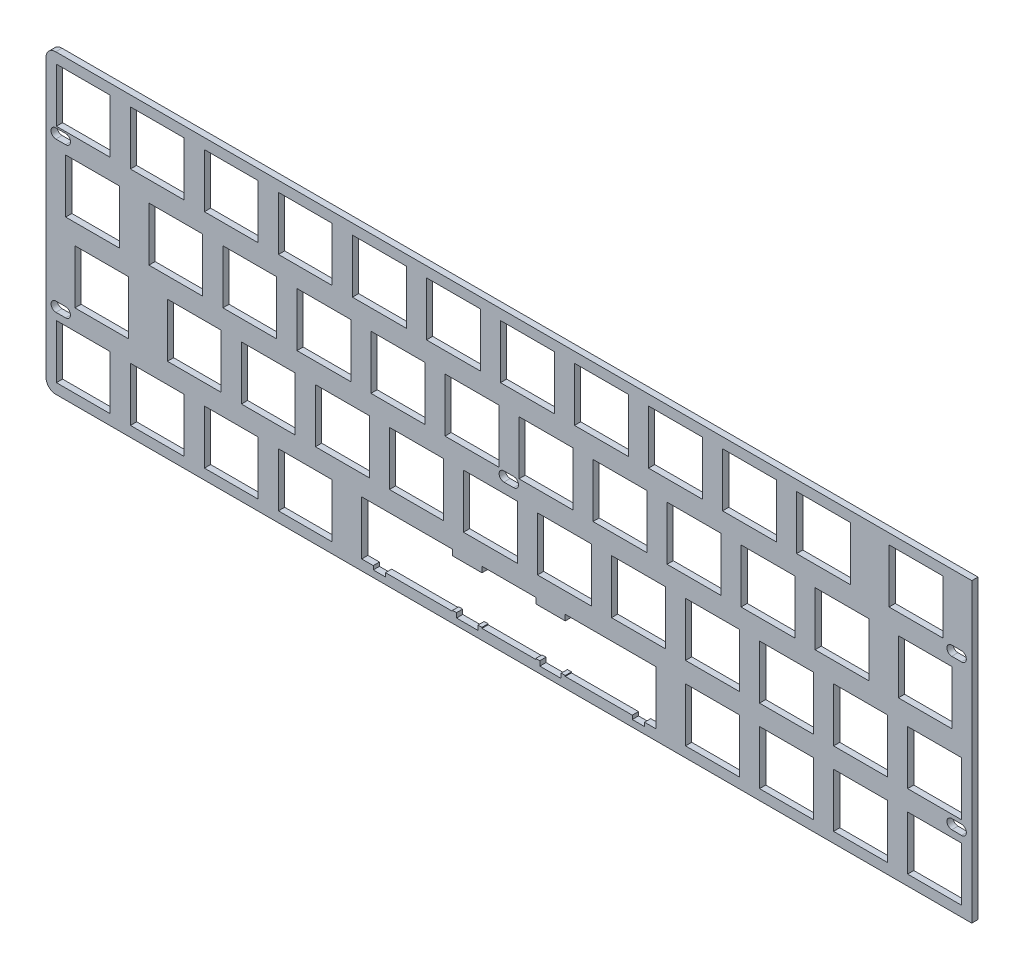
SolidWorks part; units mm, degrees
ref_plane "Front Plane" through (0, 0, 0) normal (0, 0, 1) x (1, 0, 0)
ref_plane "Top Plane" through (0, 0, 0) normal (0, 1, 0) x (1, 0, 0)
ref_plane "Right Plane" through (0, 0, 0) normal (1, 0, 0) x (0, 0, -1)
sketch "Model" plane through (0, 0, 0) normal (0, 0, 1) x (1, 0, 0)
  line L0 (0.0951, 76.4575) -> (238.37, 76.4575)
  line L1 (238.37, 76.4575) -> (238.37, 0.1075)
  line L2 (238.37, 0.1075) -> (0.0951, 0.1075)
  line L3 (0.0951, 0.1075) -> (0.0951, 76.4575)
  line L4 (81.3513, 16.6329) -> (81.3513, 2.7836)
  line L5 (81.3513, 2.7836) -> (84.3248, 2.7836)
  line L6 (84.3248, 2.7836) -> (84.3248, 1.8135)
  line L7 (84.3248, 1.8135) -> (87.4751, 1.8135)
  line L8 (87.4751, 1.8135) -> (87.4751, 2.7836)
  line L9 (87.4751, 2.7836) -> (104.725, 2.7836)
  line L10 (104.725, 2.7836) -> (104.725, 3.0138)
  line L11 (104.725, 3.0138) -> (105.756, 3.0138)
  line L12 (105.756, 3.0138) -> (105.756, 1.8135)
  line L13 (105.756, 1.8135) -> (111.275, 1.8135)
  line L14 (111.275, 1.8135) -> (111.275, 3.0138)
  line L15 (111.275, 3.0138) -> (112.306, 3.0138)
  line L16 (112.306, 3.0138) -> (112.306, 2.7836)
  line L17 (112.306, 2.7836) -> (126.157, 2.7836)
  line L18 (126.157, 2.7836) -> (126.157, 3.0138)
  line L19 (126.157, 3.0138) -> (127.187, 3.0138)
  line L20 (127.187, 3.0138) -> (127.187, 1.8135)
  line L21 (127.187, 1.8135) -> (132.707, 1.8135)
  line L22 (132.707, 1.8135) -> (132.707, 3.0138)
  line L23 (132.707, 3.0138) -> (133.737, 3.0138)
  line L24 (133.737, 3.0138) -> (133.737, 2.7836)
  line L25 (133.737, 2.7836) -> (150.987, 2.7836)
  line L26 (150.987, 2.7836) -> (150.987, 1.8135)
  line L27 (150.987, 1.8135) -> (154.138, 1.8135)
  line L28 (154.138, 1.8135) -> (154.138, 2.7836)
  line L29 (154.138, 2.7836) -> (157.113, 2.7836)
  line L30 (157.113, 2.7836) -> (157.113, 16.6329)
  line L31 (157.113, 16.6329) -> (133.737, 16.6329)
  line L32 (133.737, 16.6329) -> (133.737, 15.1639)
  line L33 (133.737, 15.1639) -> (126.157, 15.1639)
  line L34 (126.157, 15.1639) -> (126.157, 16.6329)
  line L35 (126.157, 16.6329) -> (112.306, 16.6329)
  line L36 (112.306, 16.6329) -> (112.306, 15.1639)
  line L37 (112.306, 15.1639) -> (104.725, 15.1639)
  line L38 (104.725, 15.1639) -> (104.725, 16.6329)
  line L39 (104.725, 16.6329) -> (81.3513, 16.6329)
  line L40 (221.845, 16.6329) -> (235.694, 16.6329)
  line L41 (235.694, 16.6329) -> (235.694, 2.7836)
  line L42 (235.694, 2.7836) -> (221.845, 2.7836)
  line L43 (221.845, 2.7836) -> (221.845, 16.6329)
  line L44 (202.795, 16.6329) -> (216.644, 16.6329)
  line L45 (216.644, 16.6329) -> (216.644, 2.7836)
  line L46 (216.644, 2.7836) -> (202.795, 2.7836)
  line L47 (202.795, 2.7836) -> (202.795, 16.6329)
  line L48 (183.745, 16.6329) -> (197.594, 16.6329)
  line L49 (197.594, 16.6329) -> (197.594, 2.7836)
  line L50 (197.594, 2.7836) -> (183.745, 2.7836)
  line L51 (183.745, 2.7836) -> (183.745, 16.6329)
  line L52 (164.695, 16.6329) -> (178.544, 16.6329)
  line L53 (178.544, 16.6329) -> (178.544, 2.7836)
  line L54 (178.544, 2.7836) -> (164.695, 2.7836)
  line L55 (164.695, 2.7836) -> (164.695, 16.6329)
  line L56 (59.92, 16.6329) -> (73.769, 16.6329)
  line L57 (73.769, 16.6329) -> (73.769, 2.7836)
  line L58 (73.769, 2.7836) -> (59.92, 2.7836)
  line L59 (59.92, 2.7836) -> (59.92, 16.6329)
  line L60 (40.87, 16.6329) -> (54.719, 16.6329)
  line L61 (54.719, 16.6329) -> (54.719, 2.7836)
  line L62 (54.719, 2.7836) -> (40.87, 2.7836)
  line L63 (40.87, 2.7836) -> (40.87, 16.6329)
  line L64 (21.8199, 16.6329) -> (35.669, 16.6329)
  line L65 (35.669, 16.6329) -> (35.669, 2.7836)
  line L66 (35.669, 2.7836) -> (21.8199, 2.7836)
  line L67 (21.8199, 2.7836) -> (21.8199, 16.6329)
  line L68 (2.7699, 16.6329) -> (16.6192, 16.6329)
  line L69 (16.6192, 16.6329) -> (16.6192, 2.7836)
  line L70 (16.6192, 2.7836) -> (2.7699, 2.7836)
  line L71 (2.7699, 2.7836) -> (2.7699, 16.6329)
  line L72 (221.845, 35.6828) -> (235.694, 35.6828)
  line L73 (235.694, 35.6828) -> (235.694, 21.8336)
  line L74 (235.694, 21.8336) -> (221.845, 21.8336)
  line L75 (221.845, 21.8336) -> (221.845, 35.6828)
  line L76 (202.795, 35.6828) -> (216.644, 35.6828)
  line L77 (216.644, 35.6828) -> (216.644, 21.8336)
  line L78 (216.644, 21.8336) -> (202.795, 21.8336)
  line L79 (202.795, 21.8336) -> (202.795, 35.6828)
  line L80 (183.745, 35.6828) -> (197.594, 35.6828)
  line L81 (197.594, 35.6828) -> (197.594, 21.8336)
  line L82 (197.594, 21.8336) -> (183.745, 21.8336)
  line L83 (183.745, 21.8336) -> (183.745, 35.6828)
  line L84 (164.695, 35.6828) -> (178.544, 35.6828)
  line L85 (178.544, 35.6828) -> (178.544, 21.8336)
  line L86 (178.544, 21.8336) -> (164.695, 21.8336)
  line L87 (164.695, 21.8336) -> (164.695, 35.6828)
  line L88 (145.644, 35.6828) -> (159.494, 35.6828)
  line L89 (159.494, 35.6828) -> (159.494, 21.8336)
  line L90 (159.494, 21.8336) -> (145.644, 21.8336)
  line L91 (145.644, 21.8336) -> (145.644, 35.6828)
  line L92 (126.594, 35.6828) -> (140.444, 35.6828)
  line L93 (140.444, 35.6828) -> (140.444, 21.8336)
  line L94 (140.444, 21.8336) -> (126.594, 21.8336)
  line L95 (126.594, 21.8336) -> (126.594, 35.6828)
  line L96 (107.544, 35.6828) -> (121.394, 35.6828)
  line L97 (121.394, 35.6828) -> (121.394, 21.8336)
  line L98 (121.394, 21.8336) -> (107.544, 21.8336)
  line L99 (107.544, 21.8336) -> (107.544, 35.6828)
  line L100 (88.4936, 35.6828) -> (102.344, 35.6828)
  line L101 (102.344, 35.6828) -> (102.344, 21.8336)
  line L102 (102.344, 21.8336) -> (88.4936, 21.8336)
  line L103 (88.4936, 21.8336) -> (88.4936, 35.6828)
  line L104 (69.445, 35.6828) -> (83.294, 35.6828)
  line L105 (83.294, 35.6828) -> (83.294, 21.8336)
  line L106 (83.294, 21.8336) -> (69.445, 21.8336)
  line L107 (69.445, 21.8336) -> (69.445, 35.6828)
  line L108 (50.395, 35.6828) -> (64.244, 35.6828)
  line L109 (64.244, 35.6828) -> (64.244, 21.8336)
  line L110 (64.244, 21.8336) -> (50.395, 21.8336)
  line L111 (50.395, 21.8336) -> (50.395, 35.6828)
  line L112 (31.3449, 35.6828) -> (45.194, 35.6828)
  line L113 (45.194, 35.6828) -> (45.194, 21.8336)
  line L114 (45.194, 21.8336) -> (31.3449, 21.8336)
  line L115 (31.3449, 21.8336) -> (31.3449, 35.6828)
  line L116 (7.531, 35.6828) -> (21.3817, 35.6828)
  line L117 (21.3817, 35.6828) -> (21.3817, 21.8336)
  line L118 (21.3817, 21.8336) -> (7.531, 21.8336)
  line L119 (7.531, 21.8336) -> (7.531, 35.6828)
  line L120 (219.462, 54.7328) -> (233.313, 54.7328)
  line L121 (233.313, 54.7328) -> (233.313, 40.8838)
  line L122 (233.313, 40.8838) -> (219.462, 40.8838)
  line L123 (219.462, 40.8838) -> (219.462, 54.7328)
  line L124 (198.031, 54.7328) -> (211.882, 54.7328)
  line L125 (211.882, 54.7328) -> (211.882, 40.8838)
  line L126 (211.882, 40.8838) -> (198.031, 40.8838)
  line L127 (198.031, 40.8838) -> (198.031, 54.7328)
  line L128 (178.981, 54.7328) -> (192.832, 54.7328)
  line L129 (192.832, 54.7328) -> (192.832, 40.8838)
  line L130 (192.832, 40.8838) -> (178.981, 40.8838)
  line L131 (178.981, 40.8838) -> (178.981, 54.7328)
  line L132 (159.931, 54.7328) -> (173.782, 54.7328)
  line L133 (173.782, 54.7328) -> (173.782, 40.8838)
  line L134 (173.782, 40.8838) -> (159.931, 40.8838)
  line L135 (159.931, 40.8838) -> (159.931, 54.7328)
  line L136 (140.881, 54.7328) -> (154.732, 54.7328)
  line L137 (154.732, 54.7328) -> (154.732, 40.8838)
  line L138 (154.732, 40.8838) -> (140.881, 40.8838)
  line L139 (140.881, 40.8838) -> (140.881, 54.7328)
  line L140 (121.831, 54.7328) -> (135.682, 54.7328)
  line L141 (135.682, 54.7328) -> (135.682, 40.8838)
  line L142 (135.682, 40.8838) -> (121.831, 40.8838)
  line L143 (121.831, 40.8838) -> (121.831, 54.7328)
  line L144 (102.781, 54.7328) -> (116.632, 54.7328)
  line L145 (116.632, 54.7328) -> (116.632, 40.8838)
  line L146 (116.632, 40.8838) -> (102.781, 40.8838)
  line L147 (102.781, 40.8838) -> (102.781, 54.7328)
  line L148 (83.7311, 54.7328) -> (97.5815, 54.7328)
  line L149 (97.5815, 54.7328) -> (97.5815, 40.8838)
  line L150 (97.5815, 40.8838) -> (83.7311, 40.8838)
  line L151 (83.7311, 40.8838) -> (83.7311, 54.7328)
  line L152 (64.6811, 54.7328) -> (78.5315, 54.7328)
  line L153 (78.5315, 54.7328) -> (78.5315, 40.8838)
  line L154 (78.5315, 40.8838) -> (64.6811, 40.8838)
  line L155 (64.6811, 40.8838) -> (64.6811, 54.7328)
  line L156 (45.6311, 54.7328) -> (59.4815, 54.7328)
  line L157 (59.4815, 54.7328) -> (59.4815, 40.8838)
  line L158 (59.4815, 40.8838) -> (45.6311, 40.8838)
  line L159 (45.6311, 40.8838) -> (45.6311, 54.7328)
  line L160 (26.581, 54.7328) -> (40.4315, 54.7328)
  line L161 (40.4315, 54.7328) -> (40.4315, 40.8838)
  line L162 (40.4315, 40.8838) -> (26.581, 40.8838)
  line L163 (26.581, 40.8838) -> (26.581, 54.7328)
  line L164 (5.1511, 54.7328) -> (19.0004, 54.7328)
  line L165 (19.0004, 54.7328) -> (19.0004, 40.8838)
  line L166 (19.0004, 40.8838) -> (5.1511, 40.8838)
  line L167 (5.1511, 40.8838) -> (5.1511, 54.7328)
  line L168 (217.081, 73.7828) -> (230.932, 73.7828)
  line L169 (230.932, 73.7828) -> (230.932, 59.9338)
  line L170 (230.932, 59.9338) -> (217.081, 59.9338)
  line L171 (217.081, 59.9338) -> (217.081, 73.7828)
  line L172 (193.27, 73.7828) -> (207.119, 73.7828)
  line L173 (207.119, 73.7828) -> (207.119, 59.9338)
  line L174 (207.119, 59.9338) -> (193.27, 59.9338)
  line L175 (193.27, 59.9338) -> (193.27, 73.7828)
  line L176 (174.22, 73.7828) -> (188.069, 73.7828)
  line L177 (188.069, 73.7828) -> (188.069, 59.9338)
  line L178 (188.069, 59.9338) -> (174.22, 59.9338)
  line L179 (174.22, 59.9338) -> (174.22, 73.7828)
  line L180 (155.17, 73.7828) -> (169.019, 73.7828)
  line L181 (169.019, 73.7828) -> (169.019, 59.9338)
  line L182 (169.019, 59.9338) -> (155.17, 59.9338)
  line L183 (155.17, 59.9338) -> (155.17, 73.7828)
  line L184 (136.12, 73.7828) -> (149.969, 73.7828)
  line L185 (149.969, 73.7828) -> (149.969, 59.9338)
  line L186 (149.969, 59.9338) -> (136.12, 59.9338)
  line L187 (136.12, 59.9338) -> (136.12, 73.7828)
  line L188 (117.07, 73.7828) -> (130.919, 73.7828)
  line L189 (130.919, 73.7828) -> (130.919, 59.9338)
  line L190 (130.919, 59.9338) -> (117.07, 59.9338)
  line L191 (117.07, 59.9338) -> (117.07, 73.7828)
  line L192 (98.02, 73.7828) -> (111.869, 73.7828)
  line L193 (111.869, 73.7828) -> (111.869, 59.9338)
  line L194 (111.869, 59.9338) -> (98.02, 59.9338)
  line L195 (98.02, 59.9338) -> (98.02, 73.7828)
  line L196 (78.97, 73.7828) -> (92.819, 73.7828)
  line L197 (92.819, 73.7828) -> (92.819, 59.9338)
  line L198 (92.819, 59.9338) -> (78.97, 59.9338)
  line L199 (78.97, 59.9338) -> (78.97, 73.7828)
  line L200 (59.92, 73.7828) -> (73.769, 73.7828)
  line L201 (73.769, 73.7828) -> (73.769, 59.9338)
  line L202 (73.769, 59.9338) -> (59.92, 59.9338)
  line L203 (59.92, 59.9338) -> (59.92, 73.7828)
  line L204 (40.87, 73.7828) -> (54.719, 73.7828)
  line L205 (54.719, 73.7828) -> (54.719, 59.9338)
  line L206 (54.719, 59.9338) -> (40.87, 59.9338)
  line L207 (40.87, 59.9338) -> (40.87, 73.7828)
  line L208 (21.8199, 73.7828) -> (35.669, 73.7828)
  line L209 (35.669, 73.7828) -> (35.669, 59.9338)
  line L210 (35.669, 59.9338) -> (21.8199, 59.9338)
  line L211 (21.8199, 59.9338) -> (21.8199, 73.7828)
  line L212 (2.7699, 73.7828) -> (16.6192, 73.7828)
  line L213 (16.6192, 73.7828) -> (16.6192, 59.9338)
  line L214 (16.6192, 59.9338) -> (2.7699, 59.9338)
  line L215 (2.7699, 59.9338) -> (2.7699, 73.7828)
extrude "Boss-Extrude1" add sketch "Model" along normal blind 1.6
fillet "Fillet1" radius 2.5 2 edges at (0.0951, 0.1075, 0.8) (0.0951, 76.4575, 0.8)
sketch "Sketch10" plane through (0, 0, 1.6) normal (0, 0, 1) x (1, 0, 0)
  line L0 (233.2257, 20.8643) -> (235.7275, 20.8468)
  line L1 (235.71, 18.3475) -> (233.2287, 18.3649)
  line L2 (2.5951, 0.1075) -> (238.37, 0.1075) construction
  line L3 (238.37, 0.1075) -> (238.37, 76.4575) construction
  line L4 (235.71, 57.0181) -> (233.2081, 57.0181)
  line L5 (233.2081, 59.5175) -> (235.71, 59.5175)
  line L6 (238.37, 76.4575) -> (2.5951, 76.4575) construction
  line L7 (120.46, 38.2181) -> (117.9581, 38.2181)
  line L8 (117.9581, 40.7175) -> (120.46, 40.7175)
  line L9 (5.137, 57.0181) -> (2.6351, 57.0181)
  line L10 (2.6351, 59.5175) -> (5.137, 59.5175)
  line L11 (5.137, 18.4075) -> (2.6351, 18.4075)
  line L12 (2.6351, 20.9068) -> (5.137, 20.9068)
  line L14 (0.0951, 73.9575) -> (0.0951, 2.6075) construction
  arc A0 (235.71, 18.3475) -> (235.7275, 20.8468) centre (235.7188, 19.5971) ccw
  arc A1 (233.2257, 20.8643) -> (233.2287, 18.3649) centre (233.2272, 19.6146) ccw
  arc A2 (235.71, 57.0181) -> (235.71, 59.5175) centre (235.71, 58.2678) ccw
  arc A3 (233.2081, 59.5175) -> (233.2081, 57.0181) centre (233.2081, 58.2678) ccw
  arc A4 (120.46, 38.2181) -> (120.46, 40.7175) centre (120.46, 39.4678) ccw
  arc A5 (117.9581, 40.7175) -> (117.9581, 38.2181) centre (117.9581, 39.4678) ccw
  arc A6 (5.137, 57.0181) -> (5.137, 59.5175) centre (5.137, 58.2678) ccw
  arc A7 (2.6351, 59.5175) -> (2.6351, 57.0181) centre (2.6351, 58.2678) ccw
  arc A8 (5.137, 18.4075) -> (5.137, 20.9068) centre (5.137, 19.6572) ccw
  arc A9 (2.6351, 20.9068) -> (2.6351, 18.4075) centre (2.6351, 19.6572) ccw
  dimension "D13" = 1.2497
  dimension "D14" = 1.2497
  dimension "D1" = 2.5019
  dimension "D2" = 1.2497
  dimension "D3" = 1.2497
  dimension "D4" = 2.4994
  dimension "D5" = 18.24
  dimension "D6" = 2.66
  dimension "D7" = 1.2497
  dimension "D8" = 1.2497
  dimension "D9" = 2.5019
  dimension "D10" = 2.4994
  dimension "D11" = 16.94
  dimension "D12" = 2.66
  dimension "D15" = 117.91
  dimension "D16" = 35.74
  dimension "D17" = 18.3
  dimension "D18" = 2.54
  dimension "D19" = 16.94
  dimension "D20" = 2.54
extrude "Cut-Extrude1" cut sketch "Sketch10" against normal blind 1.6
